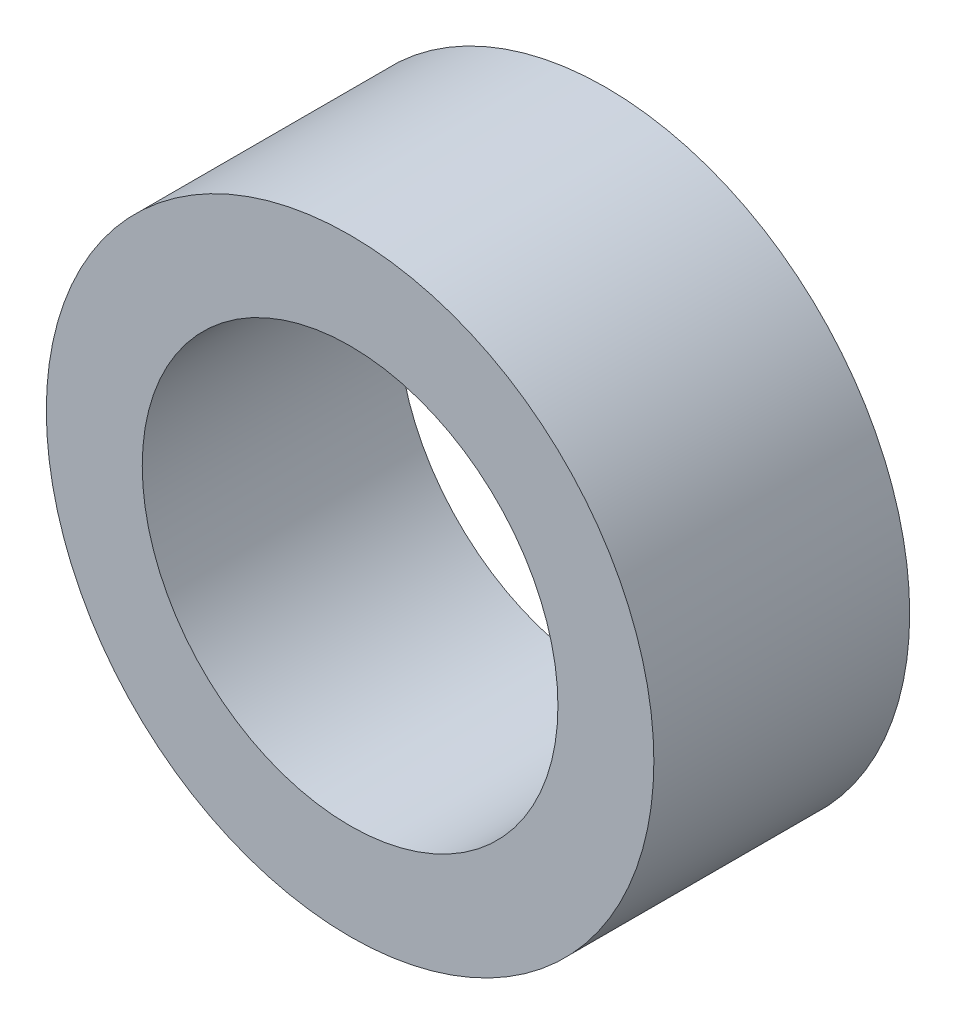
SolidWorks part; units mm, degrees
ref_plane "前视基准面" through (0, 0, 0) normal (0, 0, 1) x (1, 0, 0)
ref_plane "上视基准面" through (0, 0, 0) normal (0, 1, 0) x (1, 0, 0)
ref_plane "右视基准面" through (0, 0, 0) normal (1, 0, 0) x (0, 0, -1)
sketch "草图1" plane through (0, 0, 0) normal (0, 0, 1) x (1, 0, 0)
  circle A0 centre (0, 0) radius 4.75
  circle A1 centre (0, 0) radius 3.25
  dimension "D1" = 6.5
  dimension "D2" = 9.5
extrude "凸台-拉伸1" add sketch "草图1" along normal blind 4
